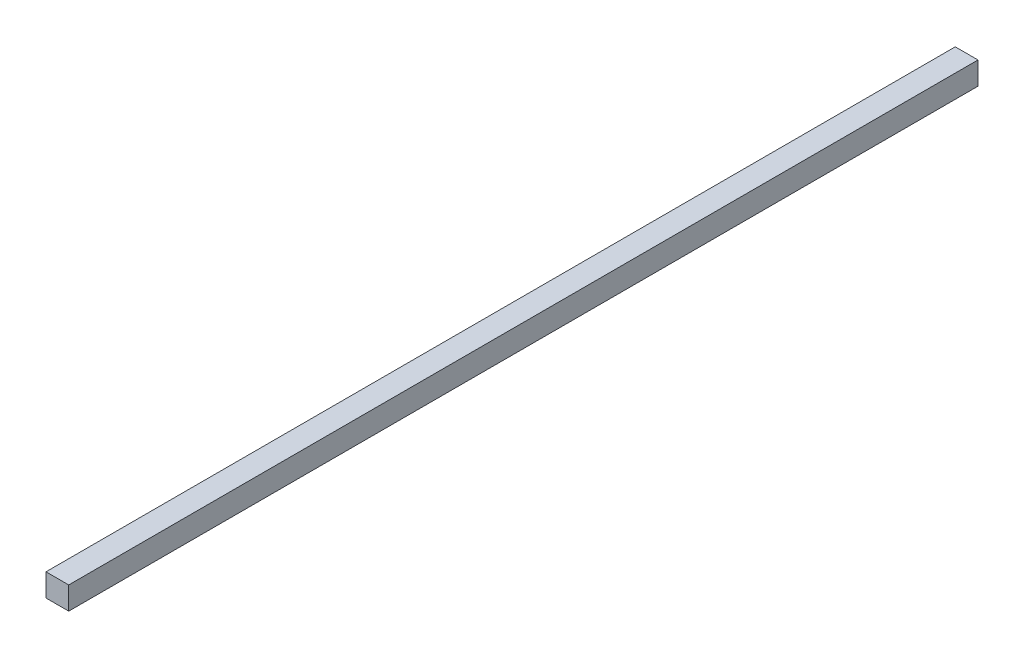
SolidWorks part; units mm, degrees
ref_plane "Front Plane" through (0, 0, 0) normal (0, 0, 1) x (1, 0, 0)
ref_plane "Top Plane" through (0, 0, 0) normal (0, 1, 0) x (1, 0, 0)
ref_plane "Right Plane" through (0, 0, 0) normal (1, 0, 0) x (0, 0, -1)
sketch "Sketch2" plane through (0, 0, 0) normal (0, 0, 1) x (1, 0, 0)
  line L1 (0, 0) -> (25.4, 0)
  line L2 (0, 0) -> (0, 25.4)
  line L3 (0, 25.4) -> (25.4, 25.4)
  line L4 (25.4, 0) -> (25.4, 25.4)
  dimension "D1" = 25.4
  dimension "D2" = 25.4
extrude "Boss-Extrude1" add sketch "Sketch2" along normal blind 1016
